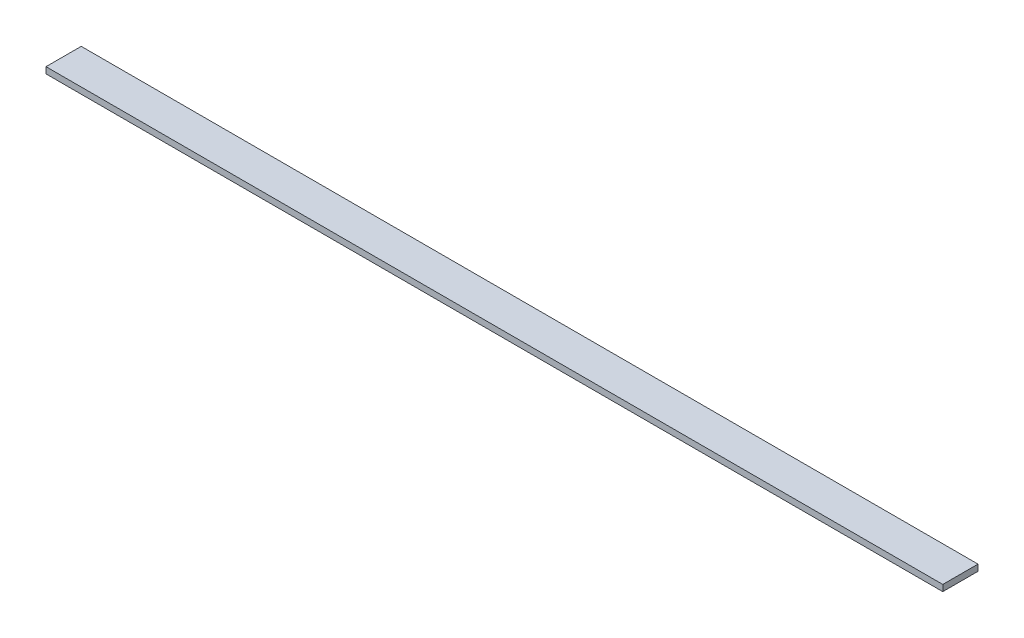
SolidWorks part; units mm, degrees
ref_plane "Front Plane" through (0, 0, 0) normal (0, 0, 1) x (1, 0, 0)
ref_plane "Top Plane" through (0, 0, 0) normal (0, 1, 0) x (1, 0, 0)
ref_plane "Right Plane" through (0, 0, 0) normal (1, 0, 0) x (0, 0, -1)
sketch "Sketch1" plane through (0, 0, 0) normal (0, 1, 0) x (1, 0, 0)
  line L1 (457.2, -17.95) -> (-457.2, -17.95)
  line L2 (457.2, -17.95) -> (457.2, 17.95)
  line L3 (457.2, 17.95) -> (-457.2, 17.95)
  line L4 (-457.2, -17.95) -> (-457.2, 17.95)
  line L5 (457.2, -17.95) -> (-457.2, 17.95) construction
  line L6 (457.2, 17.95) -> (-457.2, -17.95) construction
  point P0 (0, 0)
  dimension "D1" = 914.4
  dimension "D2" = 35.9
extrude "Boss-Extrude1" add sketch "Sketch1" along normal blind 6.4
